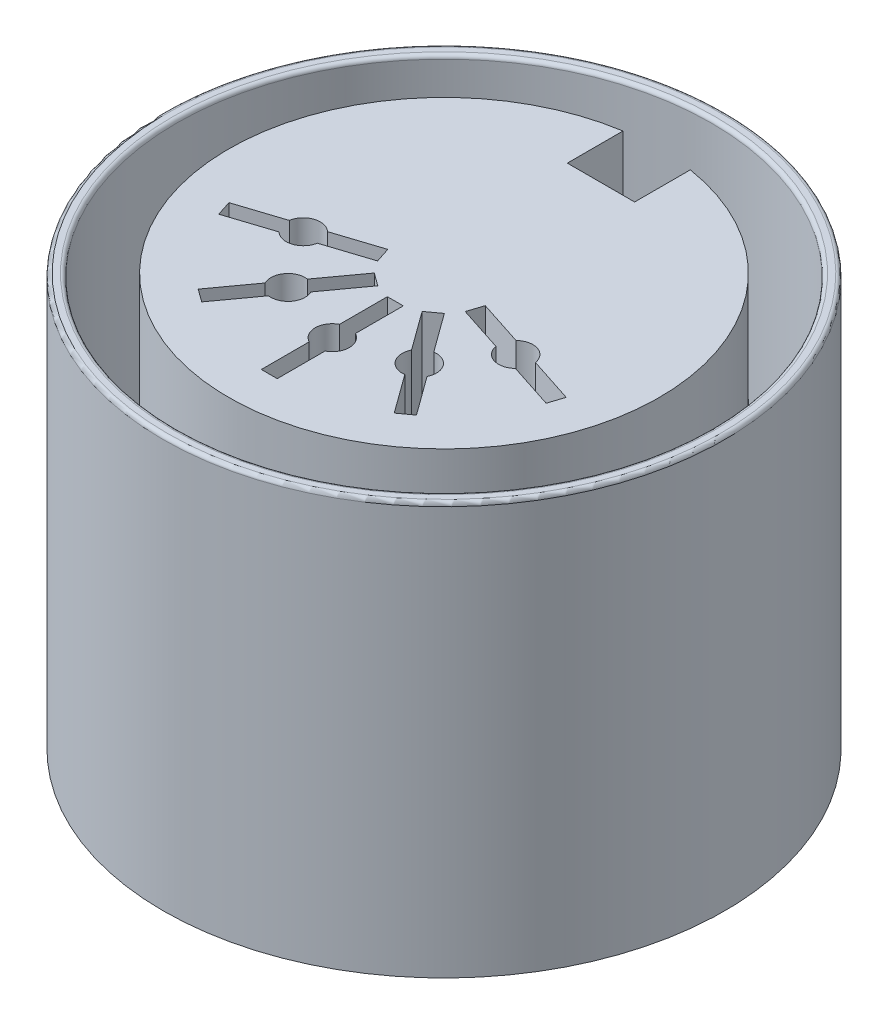
SolidWorks part; units mm, degrees
ref_plane "前视基准面" through (0, 0, 0) normal (0, 0, 1) x (1, 0, 0)
ref_plane "上视基准面" through (0, 0, 0) normal (0, 1, 0) x (1, 0, 0)
ref_plane "右视基准面" through (0, 0, 0) normal (1, 0, 0) x (0, 0, -1)
sketch "草图1" plane through (0, 0, 0) normal (0, 1, 0) x (1, 0, 0)
  circle A0 centre (0, 0) radius 5.75
  dimension "D1" = 11.5
extrude "凸台-拉伸1" add sketch "草图1" along normal blind 10
sketch "草图2" plane through (0, 10, 0) normal (0, 1, 0) x (1, 0, 0)
  line L0 (0.2125, -2.5776) -> (0.2125, -1.2994)
  line L1 (-0.2125, -2.5776) -> (-0.2125, -1.2994)
  line L2 (-0.899, 4.1924) -> (0.899, 4.1924)
  line L3 (-0.899, 4.1924) -> (-0.899, 5.8923)
  line L4 (-0.899, 5.8923) -> (0.899, 5.8923)
  line L5 (0.899, 4.1924) -> (0.899, 5.8923)
  line L6 (-0.899, 4.1924) -> (0.899, 5.8923) construction
  line L7 (-0.899, 5.8923) -> (0.899, 4.1924) construction
  line L8 (-1.3432, -2.2102) -> (-0.5919, -1.1761)
  line L9 (-0.2125, -4.6664) -> (0.2125, -4.6664)
  line L10 (-0.2125, -4.6664) -> (-0.2125, -3.3883)
  line L11 (-0.2125, -1.2994) -> (0.2125, -1.2994)
  line L12 (0.2125, -4.6664) -> (0.2125, -3.3883)
  line L13 (-1.687, -1.9604) -> (-0.9357, -0.9264)
  line L14 (-2.9148, -3.6503) -> (-2.571, -3.9001)
  line L15 (-2.9148, -3.6503) -> (-2.1635, -2.6163)
  line L16 (-0.9357, -0.9264) -> (-0.5919, -1.1761)
  line L17 (-2.571, -3.9001) -> (-1.8197, -2.8661)
  line L18 (-2.3858, -0.9986) -> (-1.1702, -0.6036)
  line L19 (-2.5171, -0.5944) -> (-1.3015, -0.1995)
  line L20 (-4.5037, -1.2399) -> (-4.3724, -1.6441)
  line L21 (-4.5037, -1.2399) -> (-3.2881, -0.8449)
  line L22 (-1.3015, -0.1995) -> (-1.1702, -0.6036)
  line L23 (-4.3724, -1.6441) -> (-3.1568, -1.2491)
  line L24 (-2.5171, 0.5944) -> (-1.3015, 0.1995) [skipped]
  line L25 (-2.3858, 0.9986) -> (-1.1702, 0.6036) [skipped]
  line L26 (-4.3724, 1.6441) -> (-4.5037, 1.2399) [skipped]
  line L27 (-4.3724, 1.6441) -> (-3.1568, 1.2491) [skipped]
  line L28 (-1.1702, 0.6036) -> (-1.3015, 0.1995) [skipped]
  line L29 (-4.5037, 1.2399) -> (-3.2881, 0.8449) [skipped]
  line L30 (-1.687, 1.9604) -> (-0.9357, 0.9264) [skipped]
  line L31 (-1.3432, 2.2102) -> (-0.5919, 1.1761) [skipped]
  line L32 (-2.571, 3.9001) -> (-2.9148, 3.6503) [skipped]
  line L33 (-2.571, 3.9001) -> (-1.8197, 2.8661) [skipped]
  line L34 (-0.5919, 1.1761) -> (-0.9357, 0.9264) [skipped]
  line L35 (-2.9148, 3.6503) -> (-2.1635, 2.6163) [skipped]
  line L36 (-0.2125, 2.5776) -> (-0.2125, 1.2994) [skipped]
  line L37 (0.2125, 2.5776) -> (0.2125, 1.2994) [skipped]
  line L38 (0.2125, 4.6664) -> (-0.2125, 4.6664) [skipped]
  line L39 (0.2125, 4.6664) -> (0.2125, 3.3883) [skipped]
  line L40 (0.2125, 1.2994) -> (-0.2125, 1.2994) [skipped]
  line L41 (-0.2125, 4.6664) -> (-0.2125, 3.3883) [skipped]
  line L42 (1.3432, 2.2102) -> (0.5919, 1.1761) [skipped]
  line L43 (1.687, 1.9604) -> (0.9357, 0.9264) [skipped]
  line L44 (2.9148, 3.6503) -> (2.571, 3.9001) [skipped]
  line L45 (2.9148, 3.6503) -> (2.1635, 2.6163) [skipped]
  line L46 (0.9357, 0.9264) -> (0.5919, 1.1761) [skipped]
  line L47 (2.571, 3.9001) -> (1.8197, 2.8661) [skipped]
  line L48 (2.3858, 0.9986) -> (1.1702, 0.6036) [skipped]
  line L49 (2.5171, 0.5944) -> (1.3015, 0.1995) [skipped]
  line L50 (4.5037, 1.2399) -> (4.3724, 1.6441) [skipped]
  line L51 (4.5037, 1.2399) -> (3.2881, 0.8449) [skipped]
  line L52 (1.3015, 0.1995) -> (1.1702, 0.6036) [skipped]
  line L53 (4.3724, 1.6441) -> (3.1568, 1.2491) [skipped]
  line L54 (2.5171, -0.5944) -> (1.3015, -0.1995)
  line L55 (2.3858, -0.9986) -> (1.1702, -0.6036)
  line L56 (4.3724, -1.6441) -> (4.5037, -1.2399)
  line L57 (4.3724, -1.6441) -> (3.1568, -1.2491)
  line L58 (1.1702, -0.6036) -> (1.3015, -0.1995)
  line L59 (4.5037, -1.2399) -> (3.2881, -0.8449)
  line L60 (1.687, -1.9604) -> (0.9357, -0.9264)
  line L61 (1.3432, -2.2102) -> (0.5919, -1.1761)
  line L62 (2.571, -3.9001) -> (2.9148, -3.6503)
  line L63 (2.571, -3.9001) -> (1.8197, -2.8661)
  line L64 (0.5919, -1.1761) -> (0.9357, -0.9264)
  line L65 (2.9148, -3.6503) -> (2.1635, -2.6163)
  arc A0 (-0.2125, -2.5776) -> (-0.2125, -3.3883) centre (0, -2.9829) ccw
  arc A1 (0.2125, -3.3883) -> (0.2125, -2.5776) centre (0, -2.9829) ccw
  arc A2 (-1.687, -1.9604) -> (-2.1635, -2.6163) centre (-1.7533, -2.4132) ccw
  arc A3 (-1.8197, -2.8661) -> (-1.3432, -2.2102) centre (-1.7533, -2.4132) ccw
  arc A4 (-2.5171, -0.5944) -> (-3.2881, -0.8449) centre (-2.8369, -0.9218) ccw
  arc A5 (-3.1568, -1.2491) -> (-2.3858, -0.9986) centre (-2.8369, -0.9218) ccw
  arc A6 (-2.3858, 0.9986) -> (-3.1568, 1.2491) centre (-2.8369, 0.9218) ccw [skipped]
  arc A7 (-3.2881, 0.8449) -> (-2.5171, 0.5944) centre (-2.8369, 0.9218) ccw [skipped]
  arc A8 (-1.3432, 2.2102) -> (-1.8197, 2.8661) centre (-1.7533, 2.4132) ccw [skipped]
  arc A9 (-2.1635, 2.6163) -> (-1.687, 1.9604) centre (-1.7533, 2.4132) ccw [skipped]
  arc A10 (0.2125, 2.5776) -> (0.2125, 3.3883) centre (0, 2.9829) ccw [skipped]
  arc A11 (-0.2125, 3.3883) -> (-0.2125, 2.5776) centre (0, 2.9829) ccw [skipped]
  arc A12 (1.687, 1.9604) -> (2.1635, 2.6163) centre (1.7533, 2.4132) ccw [skipped]
  arc A13 (1.8197, 2.8661) -> (1.3432, 2.2102) centre (1.7533, 2.4132) ccw [skipped]
  arc A14 (2.5171, 0.5944) -> (3.2881, 0.8449) centre (2.8369, 0.9218) ccw [skipped]
  arc A15 (3.1568, 1.2491) -> (2.3858, 0.9986) centre (2.8369, 0.9218) ccw [skipped]
  arc A16 (2.3858, -0.9986) -> (3.1568, -1.2491) centre (2.8369, -0.9218) ccw
  arc A17 (3.2881, -0.8449) -> (2.5171, -0.5944) centre (2.8369, -0.9218) ccw
  arc A18 (1.3432, -2.2102) -> (1.8197, -2.8661) centre (1.7533, -2.4132) ccw
  arc A19 (2.1635, -2.6163) -> (1.687, -1.9604) centre (1.7533, -2.4132) ccw
  point P0 (0, 5.0424)
  point P10 (0, -2.9829)
  point P22 (-1.7533, -2.4132)
  point P32 (-2.8369, -0.9218)
  point P42 (-2.8369, 0.9218)
  point P52 (-1.7533, 2.4132)
  point P62 (0, 2.9829)
  point P72 (1.7533, 2.4132)
  point P82 (2.8369, 0.9218)
  point P92 (2.8369, -0.9218)
  point P102 (1.7533, -2.4132)
  point P108 (0, 0)
  dimension "D1" = 10
extrude "切除-拉伸1" cut sketch "草图2" against normal blind 5
sketch "草图3" plane through (0, 0, 0) normal (0, 1, 0) x (1, 0, 0)
  circle A0 centre (0, 0) radius 7.5
  circle A1 centre (0, 0) radius 7.1433
  dimension "D1" = 15
extrude "凸台-拉伸2" add sketch "草图3" along normal blind 10 separate body
sketch "草图4" plane through (0, 0, 0) normal (0, -1, 0) x (1, 0, 0)
  circle A0 centre (0, 0) radius 7.5
extrude "凸台-拉伸3" add sketch "草图4" along normal blind 1
fillet "圆角2" radius 0.1 2 edges at (0, 10, 7.5) (0, 10, 7.1433)
